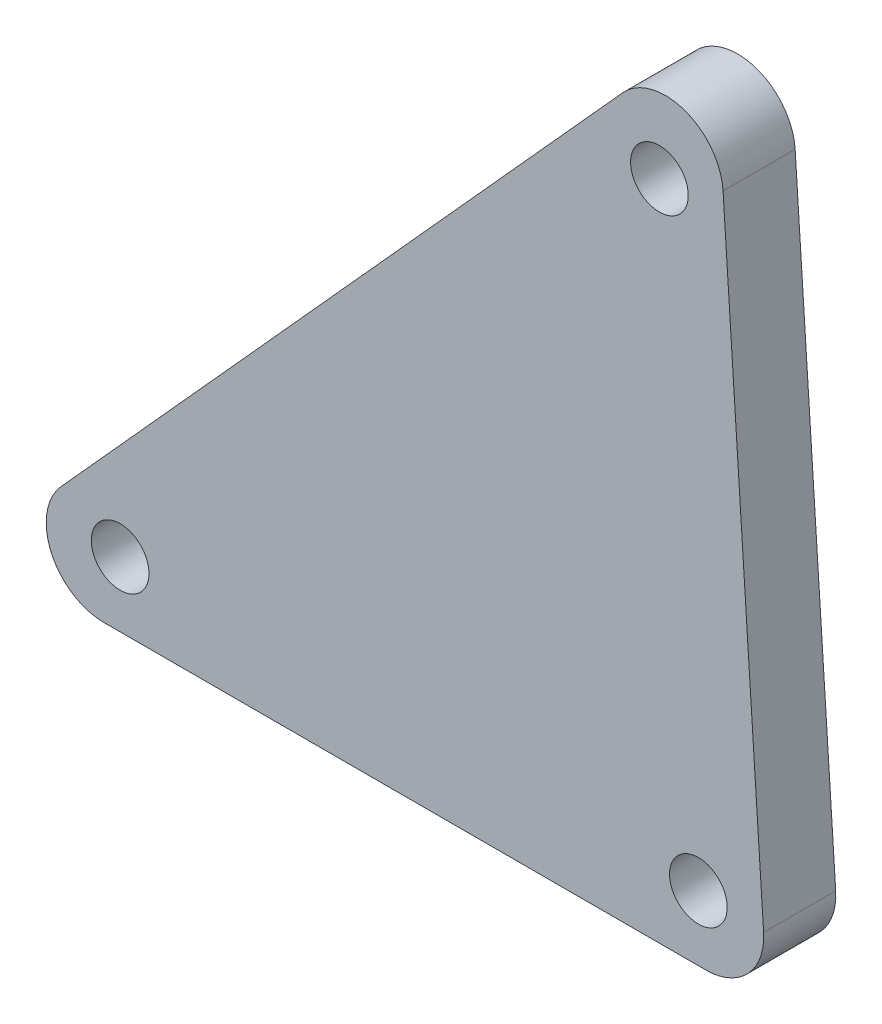
SolidWorks part; units mm, degrees
ref_plane "前基準面" through (0, 0, 0) normal (0, 0, 1) x (1, 0, 0)
ref_plane "上基準面" through (0, 0, 0) normal (0, 1, 0) x (1, 0, 0)
ref_plane "右基準面" through (0, 0, 0) normal (1, 0, 0) x (0, 0, -1)
sketch "草圖2" plane through (0, 0, 0) normal (0, 0, 1) x (1, 0, 0)
  line L0 (0, 0) -> (-37.399, -41.412) construction
  line L1 (-37.399, -41.412) -> (2.701, -41.412) construction
  line L2 (2.701, -41.412) -> (0, 0) construction
  line L3 (7.2262, -41.6517) -> (4.4135, 1.4736)
  line L4 (-2.5467, 3.8941) -> (-41.4929, -39.2311)
  line L5 (-38.5243, -45.912) -> (3.2347, -45.912)
  line L6 (-47.5264, -45.912) -> (7.5041, -45.912) construction
  line L7 (7.5041, -45.912) -> (3.7974, 10.919) construction
  line L8 (3.7974, 10.919) -> (-47.5264, -45.912) construction
  circle A0 centre (0, 0) radius 2
  circle A1 centre (2.701, -41.412) radius 2
  circle A2 centre (-37.399, -41.412) radius 2
  arc A3 (3.2347, -45.912) -> (7.2262, -41.6517) centre (3.2347, -41.912) ccw
  arc A4 (4.4135, 1.4736) -> (-2.5467, 3.8941) centre (0.4219, 1.2132) ccw
  arc A5 (-38.5243, -45.912) -> (-41.4929, -39.2311) centre (-38.5243, -41.912) cw
  dimension "D5" = 4
  dimension "D6" = 4
  dimension "D1" = 41.5
  dimension "D2" = 40.1
  dimension "D3" = 55.8
  dimension "D4" = 4.5
extrude "填料-伸長1" add sketch "草圖2" along normal mid plane 5
